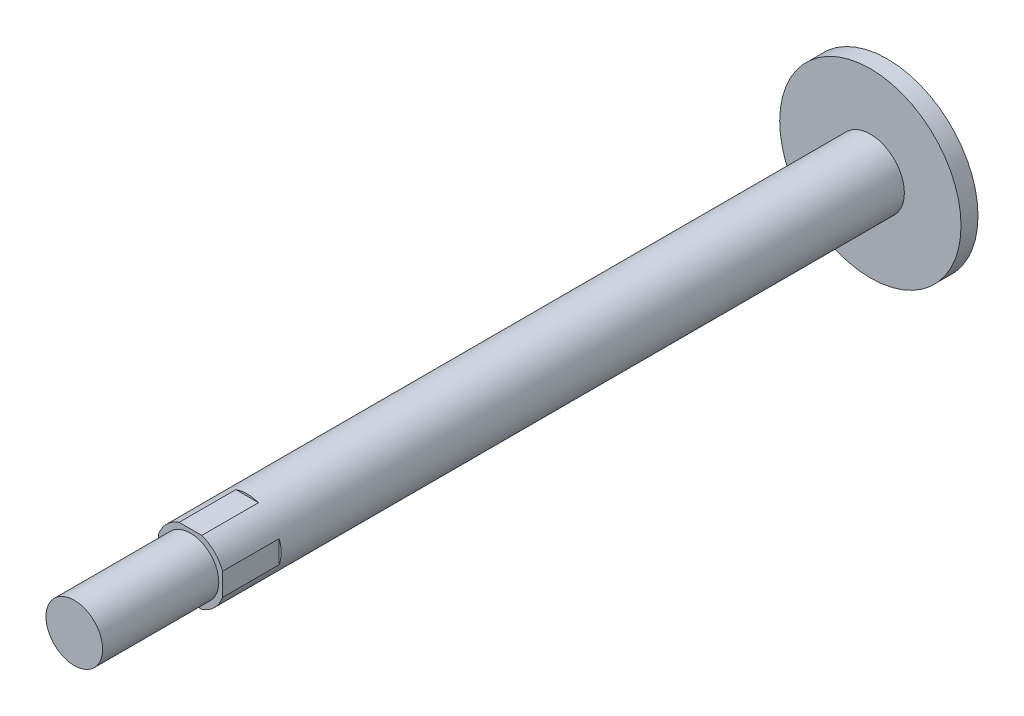
SolidWorks part; units mm, degrees
ref_plane "前视基准面" through (0, 0, 0) normal (0, 0, 1) x (1, 0, 0)
ref_plane "上视基准面" through (0, 0, 0) normal (0, 1, 0) x (1, 0, 0)
ref_plane "右视基准面" through (0, 0, 0) normal (1, 0, 0) x (0, 0, -1)
sketch "草图1" plane through (0, 0, 0) normal (1, 0, 0) x (0, 0, -1)
  line L0 (0, 0) -> (-103.5, 0) construction
  line L1 (-103.5, 0) -> (-103.5, 5)
  line L2 (-103.5, 5) -> (-95.5, 5)
  line L3 (-95.5, 5) -> (-89.5, 5)
  line L4 (-89.5, 5) -> (-81.5, 5)
  line L8 (0, 6) -> (138.5, 6)
  line L9 (-19, 6) -> (-3, 6)
  line L10 (-71.5, 6) -> (-19, 6)
  line L11 (-3, 6) -> (-3, 16)
  line L12 (-3, 16) -> (0, 16)
  line L13 (0, 16) -> (0, 0)
  line L14 (-81.5, 5) -> (-81.5, 6)
  line L17 (-81.5, 6) -> (-71.5, 6)
  line L20 (138.5, 6) -> (138.5, 5)
  line L21 (138.5, 5) -> (160.5, 5)
  line L22 (160.5, 5) -> (160.5, 0)
  line L23 (0, 0) -> (160.5, 0) construction
  line L24 (-103.5, 0) -> (160.5, 0)
  line L25 (154.5, 5) -> (154.5, 15)
  line L26 (154.5, 15) -> (109.5, 15)
  line L27 (109.5, 15) -> (109.5, 0)
  line L28 (154.5, -15) -> (109.5, -15)
  point P3 (-46.5, 6)
  point P7 (-81.5, 5)
  point P8 (-71.5, 6)
  point P11 (-102.25, 0)
  point P12 (0, 8.5)
  point P16 (-96.25, 0)
  point P17 (-103.5, 4.3285)
  point P26 (136.5, 0)
  point P29 (111.5, 0)
  point P30 (86.5, 0)
  point P31 (152.5, 5)
  point P32 (146.5, 5)
  point P33 (28.5, 0)
  point P34 (154.5, 5)
  point P39 (133.5, 15)
  dimension "缸径" = 32
  dimension "D2" = 22
  dimension "D100" = 3
  dimension "K1" = 10
  dimension "D3" = 25
  dimension "E" = 32
  dimension "V" = 12
  dimension "行程" = 25
  dimension "D5" = 25
  dimension "J" = 6
  dimension "D6" = 8
  dimension "D7" = 8
  dimension "K2" = 1.25
  dimension "K3" = 8.657
  dimension "K" = 6
  dimension "F" = 16
  dimension "G" = 27.5
  dimension "H" = 22
  dimension "I" = 17
  dimension "调整行程" = 24
  dimension "A1" = 190
  dimension "D8" = 6
  dimension "D9" = 6
  dimension "D11" = 24
  dimension "Z" = 21
  dimension "D" = 30
  dimension "W" = 10
sketch "草图2" plane through (0, 0, 0) normal (1, 0, 0) x (0, 0, -1)
  line L6 (-3, 6) -> (-3, 16) construction
  line L7 (-3, 16) -> (0, 16) construction
  line L8 (0, 16) -> (0, 0) construction
  line L9 (0, 0) -> (-143.5, 0)
  line L10 (-143.5, 0) -> (-143.5, 5)
  line L11 (-123, 5) -> (-123, 6)
  line L14 (-123, 6) -> (-3, 6)
  line L15 (-3, 6) -> (-3, 16)
  line L16 (-3, 16) -> (0, 16)
  line L17 (0, 16) -> (0, 0)
  line L18 (-123, 5) -> (-143.5, 5)
  dimension "D1" = 120
  dimension "D2" = 143.5
revolve "旋转1" add sketch "草图2" angle 360 mid plane about L9
sketch "草图3" plane through (0, 0, 143.5) normal (0, 0, 1) x (1, 0, 0)
  line L1 (0, -9.815) -> (8.5, -4.9075)
  line L2 (8.5, -4.9075) -> (8.5, 4.9075)
  line L3 (8.5, 4.9075) -> (0, 9.815)
  line L4 (0, 9.815) -> (-8.5, 4.9075)
  line L5 (-8.5, 4.9075) -> (-8.5, -4.9075)
  line L6 (-8.5, -4.9075) -> (0, -9.815)
  circle A0 centre (0, 0) radius 8.5 construction
  dimension "D1" = 17
sketch "草图5" plane through (0, 0, 143.5) normal (0, 0, 1) x (1, 0, 0)
  circle A0 centre (0, 0) radius 5 construction
  circle A1 centre (0, 0) radius 5
sketch "草图6" plane through (0, 0, 0) normal (1, 0, 0) x (0, 0, -1)
  line L0 (-143.5, 5) -> (-144.2754, 5)
  line L1 (-144.2754, 5) -> (-143.8877, 4.3285)
  line L2 (-143.8877, 4.3285) -> (-143.8877, 5) construction
  line L3 (-143.8877, 4.3285) -> (-143.5, 5)
  line L4 (-123, 5) -> (-143.5, 5) construction
  line L5 (-143.5, 5) -> (-143.5, -5) construction
  dimension "D1" = 60
sketch "草图7" plane through (0, 0, 123) normal (0, 0, 1) x (1, 0, 0)
  line L0 (0, 5) -> (0, 6) construction
  line L1 (0, 0) -> (0, 5.5) construction
  line L2 (5.6569, 2) -> (5.6569, -2)
  line L4 (-5.6569, 2) -> (-5.6569, -2)
  arc A1 (-5.6569, 2) -> (-5.6569, -2) centre (0, 0) ccw
  circle A2 centre (0, 0) radius 6 construction
  arc A3 (5.6569, -2) -> (5.6569, 2) centre (0, 0) ccw
  dimension "D1" = 4
extrude "切除-拉伸1" cut sketch "草图7" against normal blind 10
pattern_circular "阵列(圆周)1" count 4 over 360 about axis through (0, 0, 0) along (0, 0, -1) of "切除-拉伸1"
scale "缩放比例1" bodies to scale 116 scale about origin uniform scaling yes scale factor 0.75
